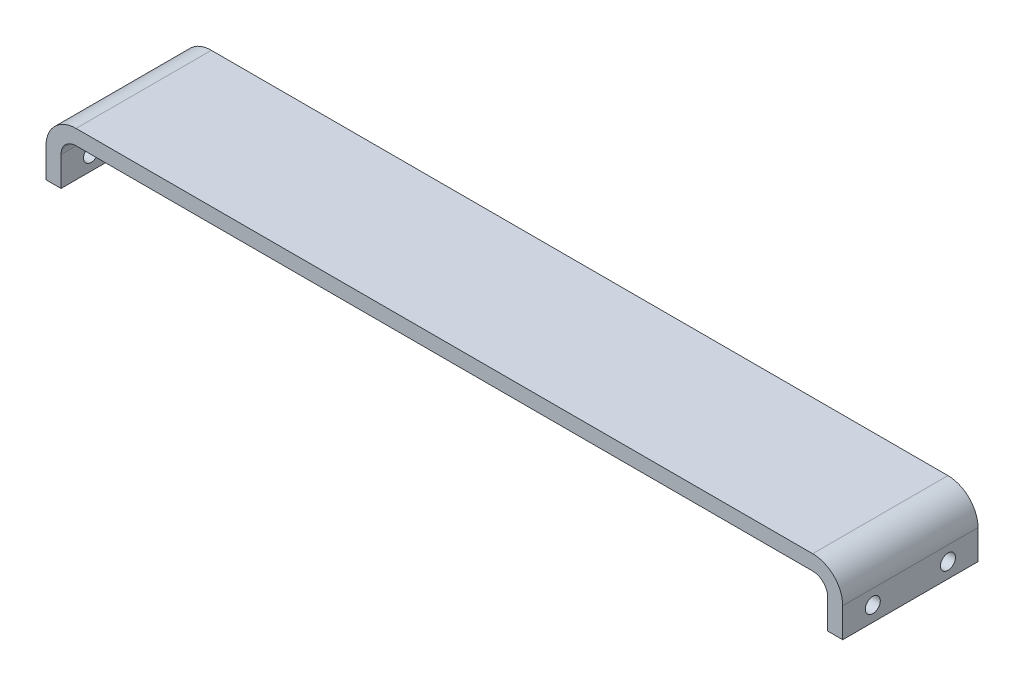
SolidWorks part; units mm, degrees
ref_plane "Front Plane" through (0, 0, 0) normal (0, 0, 1) x (1, 0, 0)
ref_plane "Top Plane" through (0, 0, 0) normal (0, 1, 0) x (1, 0, 0)
ref_plane "Right Plane" through (0, 0, 0) normal (1, 0, 0) x (0, 0, -1)
sketch "Sketch1" plane through (0, 0, 0) normal (0, 0, 1) x (1, 0, 0)
  line L0 (0, 0) -> (0, 19.6)
  line L3 (0, 19.6) -> (20, 19.6) construction
  line L4 (20, 19.6) -> (20, 39.6) construction
  line L5 (0, 0) -> (10, 0)
  line L6 (265, 0) -> (265, 41.1401) construction
  line L7 (20, 39.6) -> (510, 39.6)
  line L8 (530, 0) -> (530, 19.6)
  line L9 (0, 0) -> (10, 0)
  line L10 (20, 29.6) -> (510, 29.6)
  line L12 (10, 19.6) -> (10, 0)
  line L13 (520, 19.6) -> (520, 0)
  line L14 (520, 0) -> (530, 0)
  arc A2 (20, 39.6) -> (0, 19.6) centre (20, 19.6) ccw
  arc A3 (510, 39.6) -> (530, 19.6) centre (510, 19.6) cw
  arc A4 (20, 29.6) -> (10, 19.6) centre (20, 19.6) ccw
  arc A5 (510, 29.6) -> (520, 19.6) centre (510, 19.6) cw
  point P15 (265, 39.6)
  point P19 (265, 29.6)
  dimension "D1" = 19.6
  dimension "D2" = 20
  dimension "D4" = 530
extrude "Boss-Extrude2" add sketch "Sketch1" along normal blind 90 contours L10 A5 L13 L14 L8 A3 L7 A2 L0 L5 L12 A4
sketch "Sketch2" plane through (0, 0, 0) normal (-1, 0, 0) x (0, 0, 1)
  line L0 (90, 0) -> (0, 0) construction
  line L1 (0, 0) -> (0, 19.6) construction
  line L2 (45, 0) -> (45, 42.8019) construction
  circle A0 centre (20, 10) radius 5
  circle A1 centre (70, 10) radius 5
  dimension "D1" = 10
  dimension "D2" = 10
  dimension "D3" = 20
extrude "Cut-Extrude1" cut sketch "Sketch2" against normal through all
